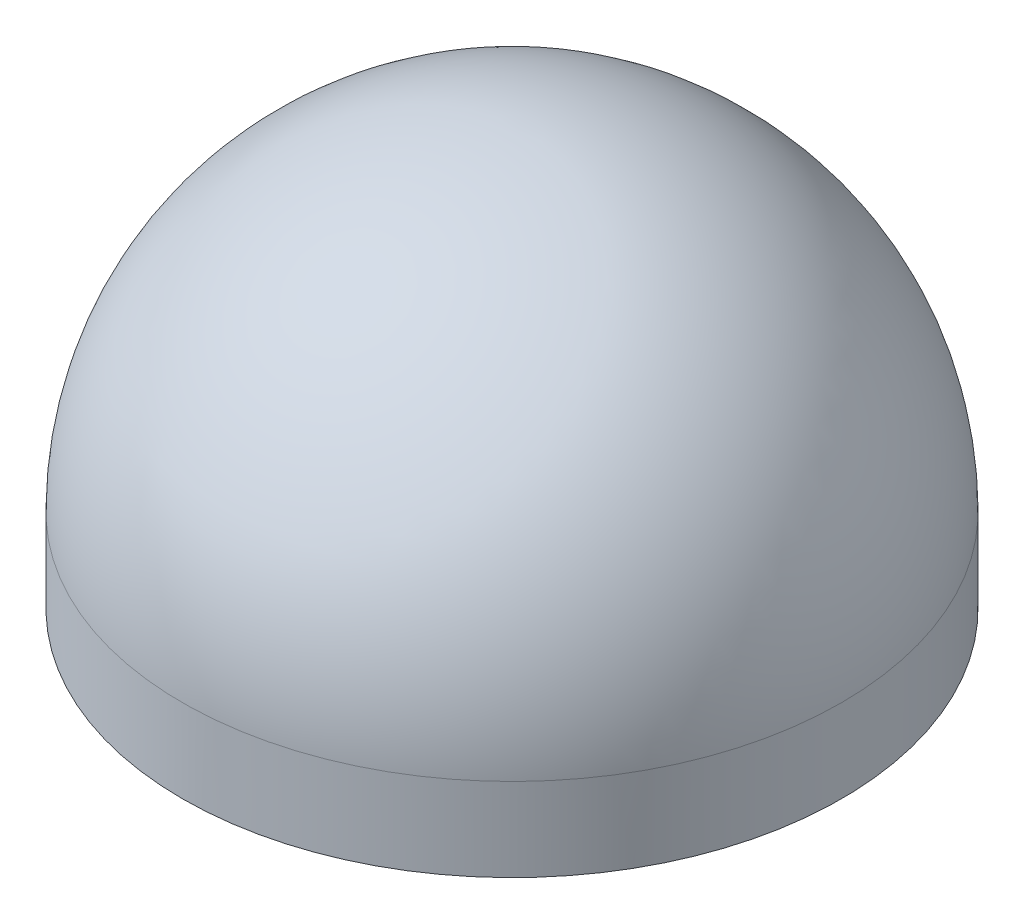
SolidWorks part; units mm, degrees
ref_plane "Front Plane" through (0, 0, 0) normal (0, 0, 1) x (1, 0, 0)
ref_plane "Top Plane" through (0, 0, 0) normal (0, 1, 0) x (1, 0, 0)
ref_plane "Right Plane" through (0, 0, 0) normal (1, 0, 0) x (0, 0, -1)
other "Configuration Table"
sketch "Sketch1" plane through (0, 0, 0) normal (0, 0, 1) x (1, 0, 0)
  line L0 (0, 0) -> (0, 59.5) construction
  line L1 (0, 0) -> (47.5, 0)
  line L2 (47.5, 0) -> (47.5, 12)
  line L3 (0, 59.5) -> (0, 0)
  arc A0 (47.5, 12) -> (0, 59.5) centre (0, 12) ccw
revolve "HMR_topu_220g_D95x59.5" add sketch "Sketch1" angle 360 about L0
